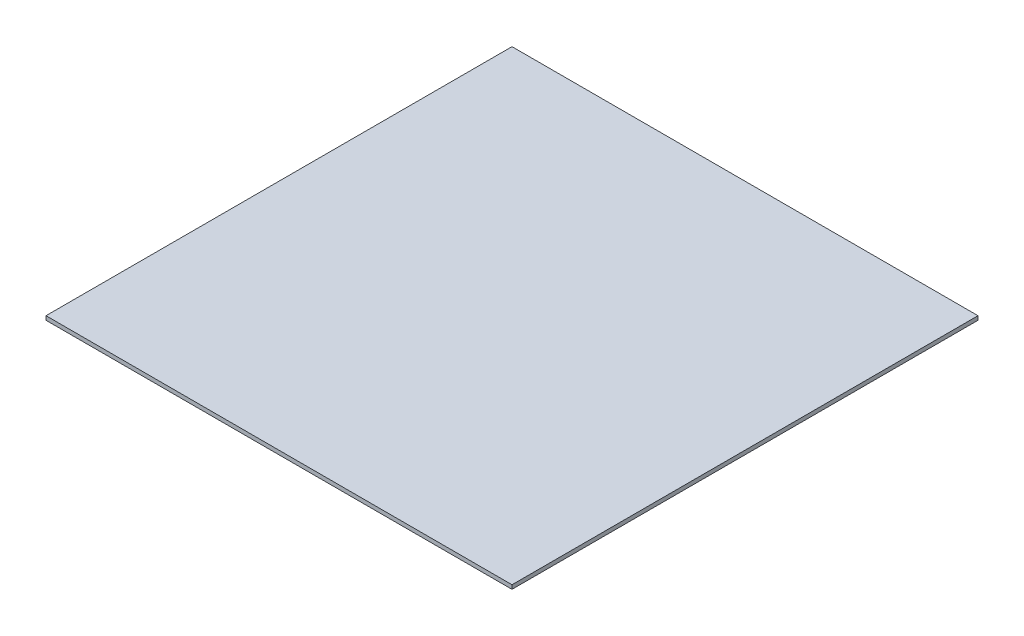
SolidWorks part; units mm, degrees
ref_plane "Plan de face" through (0, 0, 0) normal (0, 0, 1) x (1, 0, 0)
ref_plane "Plan de dessus" through (0, 0, 0) normal (0, 1, 0) x (1, 0, 0)
ref_plane "Plan de droite" through (0, 0, 0) normal (1, 0, 0) x (0, 0, -1)
sketch "Esquisse1" plane through (0, 0, 0) normal (0, 1, 0) x (1, 0, 0)
  line L1 (-175, -175) -> (175, -175)
  line L2 (-175, -175) -> (-175, 175)
  line L3 (-175, 175) -> (175, 175)
  line L4 (175, -175) -> (175, 175)
  line L5 (-175, -175) -> (175, 175) construction
  line L6 (-175, 175) -> (175, -175) construction
  point P0 (0, 0)
  dimension "D1" = 350
extrude "Boss.-Extru.1" add sketch "Esquisse1" along normal blind 3
